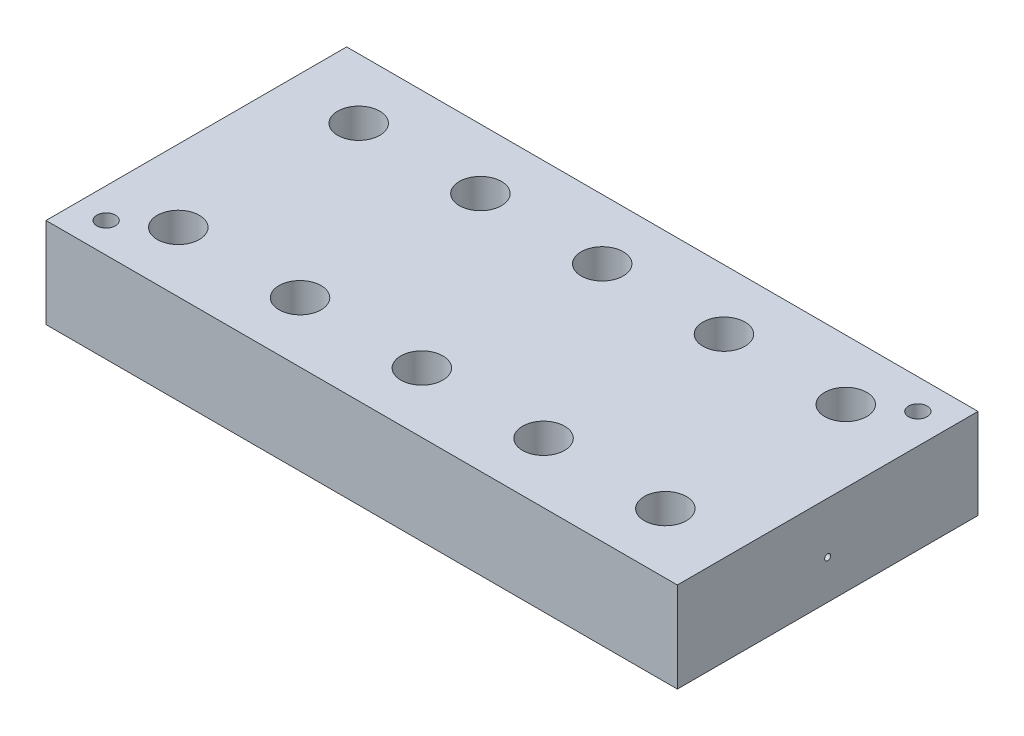
SolidWorks part; units mm, degrees
ref_plane "Front Plane" through (0, 0, 0) normal (0, 0, 1) x (1, 0, 0)
ref_plane "Top Plane" through (0, 0, 0) normal (0, 1, 0) x (1, 0, 0)
ref_plane "Right Plane" through (0, 0, 0) normal (1, 0, 0) x (0, 0, -1)
sketch "Sketch2" plane through (0, 0, 0) normal (0, 1, 0) x (1, 0, 0)
  line L0 (-46.8981, 34.5466) -> (-46.8981, -15.4534)
  line L1 (-46.8981, -15.4534) -> (58.1019, -15.4534)
  line L2 (58.1019, -15.4534) -> (58.1019, 34.5466)
  line L3 (58.1019, 34.5466) -> (-46.8981, 34.5466)
  dimension "D1" = 105
  dimension "D2" = 50
extrude "Boss-Extrude1" add sketch "Sketch2" along normal blind 15
sketch "Sketch3" plane through (0, 0, 0) normal (0, 1, 0) x (1, 0, 0)
  line L0 (74.3548, 9.5466) -> (-56.2815, 9.5466) construction
  line L1 (48.1019, 9.5466) -> (48.1019, 17.0466)
  line L2 (48.1019, 17.0466) -> (-11.8981, 17.0466)
  line L3 (-11.8981, 17.0466) -> (-11.8981, 19.5466)
  line L4 (-11.8981, 19.5466) -> (-36.8981, 19.5466)
  line L5 (-36.8981, 19.5466) -> (-36.8981, 9.5466)
  line L6 (-36.8981, 9.5466) -> (48.1019, 9.5466)
  line L7 (58.1019, -15.4534) -> (58.1019, 34.5466) construction
  line L9 (-46.8981, -15.4534) -> (58.1019, -15.4534) construction
  dimension "D1" = 60
  dimension "D2" = 25
  dimension "D3" = 10
  dimension "D4" = 25
  dimension "D5" = 10
  dimension "D6" = 7.5
sketch "Skizze7" plane through (-46.8981, 0, 0) normal (-1, 0, 0) x (0, 0, 1)
  line L1 (-34.5466, 0) -> (15.4534, 0) construction
  line L3 (-9.5466, -6.0172) -> (-9.5466, 6.0172) construction
  line L4 (15.4534, 15) -> (15.4534, 0) construction
  line L5 (-34.5466, 15) -> (-34.5466, 0) construction
  circle A0 centre (-9.5466, 7.9) radius 2.1
  dimension "D1" = 4.2
  dimension "D2" = 7.9
extrude "Schnitt-Linear austragen6" cut sketch "Skizze7" against normal blind 10
revolve "Schnitt-Rotation1" cut sketch "Sketch3" angle 360 about L0
sketch "Skizze10" plane through (0, 0, 0) normal (0, -1, 0) x (1, 0, 0)
  line L0 (48.1019, -17.0466) -> (-11.8981, -17.0466) construction
  line L1 (38.1019, -17.0466) -> (25.6019, -17.0466)
  line L2 (38.1019, -17.0466) -> (38.1019, -13.0466)
  line L3 (38.1019, -13.0466) -> (25.6019, -13.0466)
  line L4 (25.6019, -17.0466) -> (25.6019, -13.0466)
  line L5 (48.1019, -2.0466) -> (48.1019, -17.0466) construction
  line L10 (85.7448, -9.5466) -> (-66.8579, -9.5466) construction
  line L11 (-46.8981, 15.4534) -> (58.1019, 15.4534) construction
  line L12 (58.1019, -34.5466) -> (-46.8981, -34.5466) construction
  dimension "D1" = 10
  dimension "D2" = 12.5
  dimension "D5" = 4
revolve "Rotation3" add sketch "Skizze10" angle 180 about L10
sketch "Skizze11" plane through (0, 0, 0) normal (0, -1, 0) x (1, 0, 0)
  line L0 (25.6019, -17.0466) -> (-11.8981, -17.0466) construction
  line L1 (13.1019, -17.0466) -> (0.6019, -17.0466)
  line L2 (13.1019, -17.0466) -> (13.1019, -13.0466)
  line L3 (13.1019, -13.0466) -> (0.6019, -13.0466)
  line L4 (0.6019, -17.0466) -> (0.6019, -13.0466)
  line L5 (38.1019, -13.0466) -> (25.6019, -13.0466) construction
  line L6 (25.6019, -13.0466) -> (25.6019, -17.0466) construction
  line L7 (95.0378, -9.5466) -> (-94.5432, -9.5466) construction
  line L8 (-46.8981, 15.4534) -> (58.1019, 15.4534) construction
  line L9 (58.1019, -34.5466) -> (-46.8981, -34.5466) construction
  point P10 (25.6019, -15.0466)
  dimension "D1" = 12.5
  dimension "D2" = 12.5
revolve "Rotation4" add sketch "Skizze11" angle 180 about L7
sketch "Skizze12" plane through (0, 0, 0) normal (0, -1, 0) x (1, 0, 0)
  line L0 (58.1019, 15.4534) -> (58.1019, -34.5466) construction
  line L1 (-46.8981, -34.5466) -> (-46.8981, 15.4534) construction
  line L3 (-46.8981, 15.4534) -> (58.1019, 15.4534) construction
  circle A0 centre (-39.3981, 7.9534) radius 2.1
  circle A1 centre (5.6019, 7.9534) radius 2.1
  circle A2 centre (50.6019, 7.9534) radius 2.1
  dimension "D3" = 4.2
  dimension "D2" = 7.5
  dimension "D4" = 7.5
  dimension "D5" = 7.5
  dimension "D1" = 3
ref_plane "Ebene6" through (0, 0, -9.5466) normal (0, 0, 1) x (1, 0, 0)
sketch "Skizze13" plane through (-46.8981, 0, 0) normal (-1, 0, 0) x (0, 0, 1)
  line L0 (-34.5466, 0) -> (15.4534, 0) construction
  line L1 (15.4534, 15) -> (0.4534, 15)
  line L2 (15.4534, 15) -> (15.4534, 5)
  line L3 (15.4534, 5) -> (0.4534, 5)
  line L4 (0.4534, 15) -> (0.4534, 5)
  line L5 (-34.5466, 0) -> (15.4534, 0) construction
  line L6 (-34.5466, 15) -> (-19.5466, 15)
  line L7 (-34.5466, 15) -> (-34.5466, 5)
  line L8 (-34.5466, 5) -> (-19.5466, 5)
  line L9 (-19.5466, 15) -> (-19.5466, 5)
  dimension "D1" = 15
  dimension "D2" = 5
  dimension "D3" = 15
  dimension "D4" = 5
ref_plane "Plane1" through (58.1019, 0, 0) normal (1, 0, 0) x (0, 0, -1)
sketch "Sketch5" plane through (58.1019, 0, 0) normal (1, 0, 0) x (0, 0, -1)
  line L3 (-15.4534, 15) -> (-15.4534, 0) construction
  line L5 (-15.4534, 0) -> (34.5466, 0) construction
  circle A0 centre (9.5466, 6.5) radius 0.5
  point P5 (0, 0)
  point P8 (12.3353, -133.3789)
  dimension "D1" = 1
  dimension "D2" = 25
  dimension "D3" = 6.5
extrude "Cut-Extrude2" cut sketch "Sketch5" against normal up to next
sketch "Skizze14" plane through (-36.8981, 0, 0) normal (1, 0, 0) x (0, 0, -1)
  line L0 (19.5466, 0) -> (-0.4534, 0) construction
  circle A0 centre (9.5466, 0) radius 5.5
  dimension "D1" = 11
sketch "Skizze15" plane through (48.1019, 0, 0) normal (-1, 0, 0) x (0, 0, 1)
  line L0 (-2.0466, 0) -> (-17.0466, 0) construction
  circle A0 centre (-9.5466, 0) radius 4
  dimension "D1" = 8
loft "Schnitt-Ausformung1" cut profiles "Skizze14", "Skizze15"
fillet "Verrundung1" radius 1 10 edges at (38.1019, 4.1765, -9.5466) (25.6019, 4.3971, -9.5466) (13.1019, 4.6176, -9.5466) (0.6019, 4.8382, -9.5466) (38.1019, 7.5, -9.5466) (13.1019, 7.5, -9.5466) (25.6019, 7.5, -9.5466) (-11.8981, 10, -9.5466) (-11.8981, 7.5, -9.5466) (0.6019, 7.5, -9.5466)
sketch "Skizze20" plane through (0, 0, 0) normal (0, -1, 0) x (1, 0, 0)
  line L0 (58.1019, -34.5466) -> (-46.8981, -34.5466) construction
  line L1 (58.1019, 15.4534) -> (58.1019, -34.5466) construction
  line L2 (-46.8981, -34.5466) -> (-46.8981, 15.4534) construction
  line L3 (-46.8981, 15.4534) -> (58.1019, 15.4534) construction
  circle A0 centre (53.1019, -29.5466) radius 1.55
  circle A1 centre (-41.8981, 10.4534) radius 1.55
  point P6 (0, 0)
  dimension "D1" = 3.1
  dimension "D2" = 5
  dimension "D3" = 5
  dimension "D4" = 5
  dimension "D5" = 5
extrude "Ausrichtungsstifte" cut sketch "Skizze20" against normal up to next
hole_wizard "Stirnsenkung für M3 Flachkopfschraube mit Schlitz2" positions "Skizze21" profile "Skizze22" counterbore size "M3" standard "DIN" end condition through all
sketch "Skizze21" plane through (0, 15, 0) normal (0, 1, 0) x (1, 0, 0)
  line L0 (58.1019, 34.5466) -> (-46.8981, 34.5466) construction
  line L1 (58.1019, -15.4534) -> (58.1019, 34.5466) construction
  point P63 (46.1019, 24.5466)
  point P77 (25.8519, 24.5466)
  point P78 (5.6019, 24.5466)
  point P79 (-14.6481, 24.5466)
  point P80 (-34.8981, 24.5466)
  point P81 (25.8519, -5.4534)
  point P82 (5.6019, -5.4534)
  point P83 (-14.6481, -5.4534)
  point P84 (-34.8981, -5.4534)
  point P85 (46.1019, -5.4534)
  dimension "D1" = 10
  dimension "D2" = 12
  dimension "D3" = 5
  dimension "D4" = 2
sketch "Skizze22" plane through (46.1019, 15, -24.5466) normal (1, 0, 0) x (0, 0, 1)
  line L0 (0, 0) -> (0, 15)
  line L1 (0, 15) -> (1.7, 15)
  line L3 (1.7, 15) -> (1.7, 9.9)
  line L4 (1.7, 9.9) -> (3.5, 9.9)
  line L5 (3.5, 9.9) -> (3.5, 0)
  line L7 (3.5, 0) -> (0, 0)
  line L11 (0, -6.35) -> (0, 107.95) construction
  dimension "Bohrerdurchmesser" = 3.4
  dimension "Bohrungstiefe" = 15
  dimension "Senkdurchmesser2" = 7
  dimension "Senktiefe2" = 9.9
